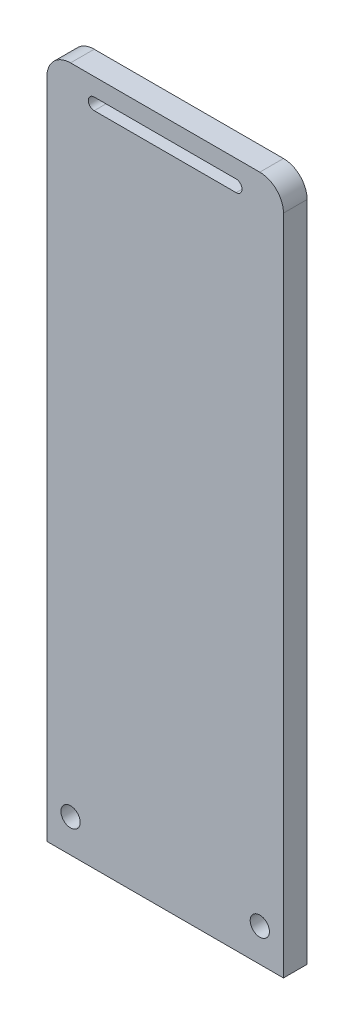
SolidWorks part; units mm, degrees
material "1060 Alloy"
ref_plane "Front Plane" through (0, 0, 0) normal (0, 0, 1) x (1, 0, 0)
ref_plane "Top Plane" through (0, 0, 0) normal (0, 1, 0) x (1, 0, 0)
ref_plane "Right Plane" through (0, 0, 0) normal (1, 0, 0) x (0, 0, -1)
sketch "Sketch1" plane through (0, 0, 0) normal (0, 0, 1) x (1, 0, 0)
  line L0 (0, 184.15) -> (0, 0) construction
  line L1 (-31.75, 0) -> (31.75, 0)
  line L2 (-31.75, 0) -> (-31.75, 184.15)
  line L3 (-31.75, 184.15) -> (31.75, 184.15)
  line L4 (31.75, 0) -> (31.75, 184.15)
  dimension "D1" = 63.5
  dimension "D2" = 184.15
extrude "Boss-Extrude1" add sketch "Sketch1" along normal mid plane 6.35
sketch "Sketch3" plane through (0, 0, -3.175) normal (0, 0, -1) x (-1, 0, 0)
  line L0 (31.75, 0) -> (-31.75, 0) construction
  line L1 (-25.4, 8.89) -> (25.4, 8.89) construction
  line L2 (0, 0) -> (0, 8.89) construction
  circle A0 centre (-25.4, 8.89) radius 2.5797
  circle A1 centre (25.4, 8.89) radius 2.5797
  dimension "D1" = 5.1594
  dimension "D2" = 50.8
  dimension "D3" = 8.89
extrude "Cut-Extrude2" cut sketch "Sketch3" against normal through all
sketch "Sketch4" plane through (0, 0, -3.175) normal (0, 0, -1) x (-1, 0, 0)
  line L0 (-19.05, 177.8) -> (19.05, 177.8) construction
  line L1 (-19.05, 179.3875) -> (19.05, 179.3875)
  line L2 (-19.05, 176.2125) -> (19.05, 176.2125)
  line L3 (0, 184.15) -> (0, 0) construction
  line L4 (-31.75, 184.15) -> (31.75, 184.15) construction
  line L5 (31.75, 0) -> (-31.75, 0) construction
  arc A0 (-19.05, 179.3875) -> (-19.05, 176.2125) centre (-19.05, 177.8) ccw
  arc A1 (19.05, 176.2125) -> (19.05, 179.3875) centre (19.05, 177.8) ccw
  point P2 (0, 177.8)
  dimension "D1" = 3.175
  dimension "D2" = 38.1
extrude "Cut-Extrude3" cut sketch "Sketch4" against normal through all
fillet "Fillet1" radius 6.35 2 edges at (-31.75, 184.15, 0) (31.75, 184.15, 0)
